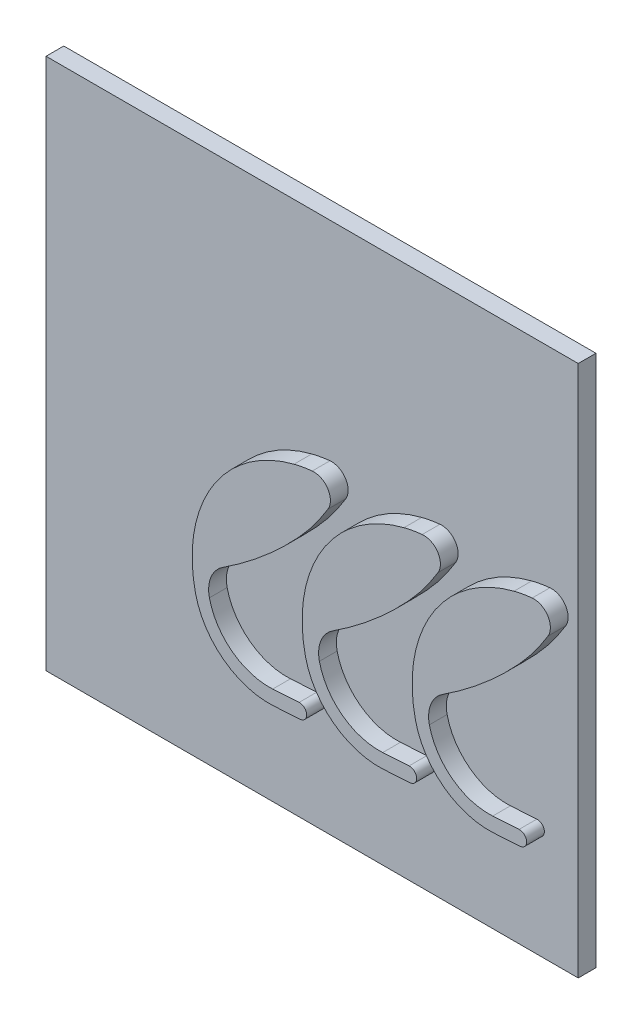
SolidWorks part; units mm, degrees
material "Obyčejná uhlíková ocel"
ref_plane "Přední rovina" through (0, 0, 0) normal (0, 0, 1) x (1, 0, 0)
ref_plane "Horní rovina" through (0, 0, 0) normal (0, 1, 0) x (1, 0, 0)
ref_plane "Pravá rovina" through (0, 0, 0) normal (1, 0, 0) x (0, 0, -1)
sketch "Skica1" plane through (0, 0, 0) normal (0, 0, 1) x (1, 0, 0)
  line L1 (0, 0) -> (300, 0)
  line L2 (0, 0) -> (0, 300)
  line L3 (0, 300) -> (300, 300)
  line L4 (300, 0) -> (300, 300)
  dimension "D1" = 300
extrude "Přidat vysunutím1" add sketch "Skica1" along normal blind 10
sketch "Skica3" plane through (0, 0, 10) normal (0, 0, 1) x (1, 0, 0)
  line L6 (153.1575, 57.9044) -> (138.2907, 56.9809)
  line L8 (152.6615, 65.889) -> (137.7947, 64.9655)
  line L21 (102.0878, 25.1207) -> (231.0679, 25.1207) construction
  line L22 (215.1575, 57.9044) -> (200.2907, 56.9809)
  line L23 (214.6615, 65.889) -> (199.7947, 64.9655)
  line L24 (277.1575, 57.9044) -> (262.2907, 56.9809)
  line L25 (276.6615, 65.889) -> (261.7947, 64.9655)
  arc A0 (160.0455, 182.5328) -> (149.7881, 180.7378) centre (166.6861, 114.3791) ccw
  arc A1 (149.7881, 180.7378) -> (94.2891, 89.8786) centre (168.5987, 106.8681) ccw
  arc A2 (94.2891, 89.8786) -> (138.2907, 56.9809) centre (135.6596, 99.3372) ccw
  arc A3 (160.0455, 182.5328) -> (168.9632, 168.3939) centre (160.9526, 173.2231) cw
  arc A5 (102.0878, 91.6617) -> (137.7947, 64.9655) centre (135.6596, 99.3372) ccw
  arc A8 (152.6615, 65.889) -> (153.1575, 57.9044) centre (152.9095, 61.8967) cw
  arc A9 (102.0878, 91.6617) -> (109.6232, 110.269) centre (119.1797, 95.5694) cw
  arc A10 (109.6232, 110.269) -> (152.4561, 146.4089) centre (-13.4818, 299.6252) ccw
  arc A11 (152.4561, 146.4089) -> (168.9632, 168.3939) centre (52.8052, 238.4201) ccw
  arc A12 (164.0878, 91.6617) -> (199.7947, 64.9655) centre (197.6596, 99.3372) ccw
  arc A13 (156.2891, 89.8786) -> (200.2907, 56.9809) centre (197.6596, 99.3372) ccw
  arc A14 (214.6615, 65.889) -> (215.1575, 57.9044) centre (214.9095, 61.8967) cw
  arc A15 (164.0878, 91.6617) -> (171.6232, 110.269) centre (181.1797, 95.5694) cw
  arc A16 (211.7881, 180.7378) -> (156.2891, 89.8786) centre (230.5987, 106.8681) ccw
  arc A17 (171.6232, 110.269) -> (214.4561, 146.4089) centre (48.5182, 299.6252) ccw
  arc A18 (214.4561, 146.4089) -> (230.9632, 168.3939) centre (114.8052, 238.4201) ccw
  arc A19 (222.0455, 182.5328) -> (230.9632, 168.3939) centre (222.9526, 173.2231) cw
  arc A20 (222.0455, 182.5328) -> (211.7881, 180.7378) centre (228.6861, 114.3791) ccw
  arc A21 (226.0878, 91.6617) -> (261.7947, 64.9655) centre (259.6596, 99.3372) ccw
  arc A22 (218.2891, 89.8786) -> (262.2907, 56.9809) centre (259.6596, 99.3372) ccw
  arc A23 (276.6615, 65.889) -> (277.1575, 57.9044) centre (276.9095, 61.8967) cw
  arc A24 (226.0878, 91.6617) -> (233.6232, 110.269) centre (243.1797, 95.5694) cw
  arc A25 (273.7881, 180.7378) -> (218.2891, 89.8786) centre (292.5987, 106.8681) ccw
  arc A26 (233.6232, 110.269) -> (276.4561, 146.4089) centre (110.5182, 299.6252) ccw
  arc A27 (276.4561, 146.4089) -> (292.9632, 168.3939) centre (176.8052, 238.4201) ccw
  arc A28 (284.0455, 182.5328) -> (292.9632, 168.3939) centre (284.9526, 173.2231) cw
  arc A29 (284.0455, 182.5328) -> (273.7881, 180.7378) centre (290.6861, 114.3791) ccw
  dimension "D1" = 3
extrude "Přidat vysunutím3" add sketch "Skica3" along normal blind 10
